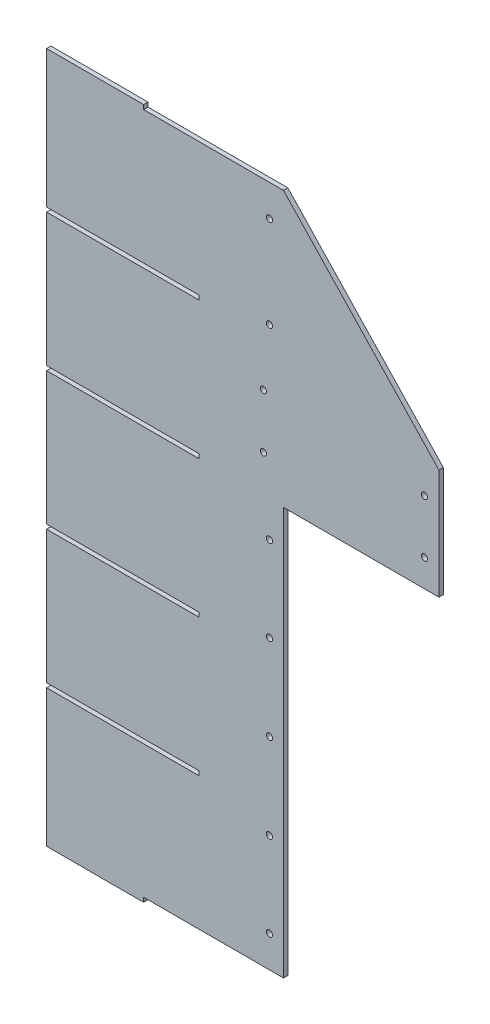
SolidWorks part; units mm, degrees
material "6061-T6 (SS)"
ref_plane "X-Y Datum" through (0, 0, 0) normal (0, 0, 1) x (1, 0, 0)
ref_plane "X-Z Datum" through (0, 0, 0) normal (0, 1, 0) x (1, 0, 0)
ref_plane "Y-Z Datum" through (0, 0, 0) normal (1, 0, 0) x (0, 0, -1)
sketch "Sketch1" plane through (0, 0, 0) normal (0, 0, 1) x (1, 0, 0)
  line L1 (129.0131, 254.2454) -> (-18.6854, 254.2454)
  line L3 (129.0131, -241.3467) -> (-18.6854, -241.3467)
  line L4 (-18.6854, 254.2454) -> (-18.6854, 157.667)
  line L24 (129.0131, 254.2454) -> (129.0131, -241.3467)
  line L25 (92.0885, 157.667) -> (-18.6854, 157.667)
  line L27 (92.0885, 154.492) -> (-18.6854, 154.492)
  line L29 (92.0885, 57.9136) -> (-18.6854, 57.9136)
  line L31 (92.0885, 54.7386) -> (-18.6854, 54.7386)
  line L33 (92.0885, -41.8399) -> (-18.6854, -41.8399)
  line L35 (92.0885, -45.0149) -> (-18.6854, -45.0149)
  line L37 (92.0885, -141.5933) -> (-18.6854, -141.5933)
  line L39 (92.0885, -144.7683) -> (-18.6854, -144.7683)
  line L41 (92.0885, -141.5933) -> (92.0885, -144.7683)
  line L42 (92.0885, -41.8399) -> (92.0885, -45.0149)
  line L43 (92.0885, 57.9136) -> (92.0885, 54.7386)
  line L44 (-18.6854, -144.7683) -> (-18.6854, -241.3467)
  line L45 (-18.6854, -45.0149) -> (-18.6854, -141.5933)
  line L46 (-18.6854, 54.7386) -> (-18.6854, -41.8399)
  line L47 (-18.6854, 154.492) -> (-18.6854, 57.9136)
  line L48 (92.0885, 157.667) -> (92.0885, 154.492)
extrude "Boss-Extrude2" add sketch "Sketch1" along normal blind 3.175
sketch "Sketch4" plane through (0, 0, 3.175) normal (0, 0, 1) x (1, 0, 0)
  line L0 (129.0131, 254.2454) -> (153.4072, 240.1614) construction
  line L2 (129.0131, 254.2454) -> (129.0131, -241.3467)
  line L4 (153.4072, 240.1614) -> (153.4072, -227.2627)
  line L6 (153.4072, -227.2627) -> (153.4072, -241.3467)
  line L7 (153.4072, -241.3467) -> (129.0131, -241.3467)
  line L8 (129.0131, 254.2454) -> (153.4072, 254.2454)
  line L9 (153.4072, 254.2454) -> (153.4072, 240.1614)
extrude "Boss-Extrude3" add sketch "Sketch4" against normal through all
sketch "Sketch7" plane through (0, 0, 3.175) normal (0, 0, 1) x (1, 0, 0)
  line L0 (51.8072, -241.3467) -> (-18.6854, -241.3467)
  line L1 (51.8072, -244.5217) -> (51.8072, -241.3467)
  line L2 (153.4072, -244.5217) -> (51.8072, -244.5217)
  line L3 (153.4072, -244.5217) -> (153.4072, -257.2217)
  line L4 (153.4072, -257.2217) -> (30.4963, -257.2217)
  line L5 (30.4963, -257.2217) -> (6.7146, -273.4777)
  line L6 (-18.6854, -273.4777) -> (6.7146, -273.4777)
  line L7 (-18.6854, -241.3467) -> (-18.6854, -273.4777)
  point P0 (-51.634, -260.9767)
  point P9 (-18.6854, -241.3467)
extrude "Boss-Extrude6" [suppressed] add sketch "Sketch7" against normal through all
sketch "Sketch8" [suppressed] plane through (0, 0, 3.175) normal (0, 0, 1) x (1, 0, 0)
  line L1 (153.4072, -257.2217) -> (221.7231, -257.2217)
  line L2 (153.4072, -257.2217) -> (153.4072, -244.5217)
  line L3 (153.4072, -244.5217) -> (221.7231, -244.5217)
  line L4 (221.7231, -257.2217) -> (221.7231, -244.5217)
  line L5 (153.4072, -241.3467) -> (221.7231, -241.3467)
  line L6 (153.4072, -241.3467) -> (153.4072, -144.7683)
  line L7 (153.4072, -144.7683) -> (221.7231, -144.7683)
  line L8 (221.7231, -241.3467) -> (221.7231, -144.7683)
  dimension "D1" = 68.3158
extrude "Boss-Extrude7" [suppressed] add sketch "Sketch8" against normal through all
sketch "Sketch11" plane through (0, 0, 3.175) normal (0, 0, 1) x (1, 0, 0)
  line L0 (92.0885, 54.7386) -> (153.4072, 54.7386) construction
  line L2 (153.4072, -241.3467) -> (153.4072, 254.2454) construction
  line L3 (266.4372, 134.68) -> (266.4372, 54.7386)
  line L4 (266.4372, 54.7386) -> (153.4072, 54.7386)
  line L5 (153.4072, 54.7386) -> (153.4072, 134.68)
  line L6 (153.4072, -241.3467) -> (153.4072, 254.2454) construction
  line L7 (153.4072, 254.2454) -> (266.4372, 134.68)
  line L8 (153.4072, 254.2454) -> (153.4072, 134.68)
extrude "Boss-Extrude8" add sketch "Sketch11" against normal through all
sketch "Sketch12" plane through (0, 0, 0) normal (0, 0, -1) x (-1, 0, 0)
  line L1 (18.6854, 254.2454) -> (-51.8072, 254.2454)
  line L2 (18.6854, 254.2454) -> (18.6854, 257.4204)
  line L3 (18.6854, 257.4204) -> (-51.8072, 257.4204)
  line L4 (-51.8072, 254.2454) -> (-51.8072, 257.4204)
  line L5 (18.6854, -241.3467) -> (-51.8072, -241.3467)
  line L6 (18.6854, -241.3467) -> (18.6854, -244.5217)
  line L7 (18.6854, -244.5217) -> (-51.8072, -244.5217)
  line L8 (-51.8072, -241.3467) -> (-51.8072, -244.5217)
extrude "Boss-Extrude9" add sketch "Sketch12" against normal through all
sketch "Sketch14" plane through (0, 0, 3.175) normal (0, 0, 1) x (1, 0, 0)
  line L0 (-18.6854, -244.5217) -> (269.694, -244.5217)
  line L1 (-18.6854, -244.5217) -> (-18.6854, 277.9004)
  line L2 (-18.6854, 277.9004) -> (269.694, 277.9004)
  line L3 (269.694, -244.5217) -> (269.694, 277.9004)
  point P0 (143.2472, -231.1146)
  point P1 (143.2472, -158.2226)
  point P2 (143.2472, -85.3305)
  point P3 (143.2472, -12.4385)
  point P4 (143.2472, 60.4536)
  point P5 (170.6792, 87.8856)
  point P6 (210.7117, 87.8856)
  point P7 (250.7441, 87.8856)
  point P8 (256.2772, 93.4187)
  point P9 (256.2772, 119.6462)
  point P10 (256.2772, 145.8738)
  point P11 (143.2472, 173.5725)
  point P12 (143.2472, 208.7929)
  point P13 (143.2472, 244.0133)
sketch "Sketch15" plane through (0, 0, 3.175) normal (0, 0, 1) x (1, 0, 0)
  line L0 (-18.6854, 257.4204) -> (23.3644, 257.4204) construction
  line L1 (-18.6854, 257.4204) -> (-18.6854, 239.7041) construction
  line L2 (-18.6854, 239.7041) -> (23.3644, 239.7041) construction
  line L3 (23.3644, 257.4204) -> (23.3644, 239.7041) construction
  line L4 (258.5632, 130.1671) -> (255.7997, 130.1671) construction
  line L5 (255.7997, 130.1671) -> (255.7997, 113.344) construction
  circle A0 centre (143.2472, 231.3133) radius 2.25
  circle A1 centre (143.2472, 164.652) radius 2.25
  circle A2 centre (255.7997, 113.344) radius 2.25
  circle A3 centre (255.7997, 74.4957) radius 2.25
  circle A4 centre (143.2472, 29.3386) radius 2.25
  circle A5 centre (143.2472, -32.3342) radius 2.25
  circle A6 centre (143.2472, -94.538) radius 2.25
  circle A7 centre (143.2472, -156.7418) radius 2.25
  circle A8 centre (143.2472, -218.4146) radius 2.25
  point P0 (143.2472, 231.3133)
  point P1 (143.2472, 164.652)
  point P2 (255.7997, 113.344)
  point P3 (255.7997, 74.4957)
  point P4 (143.2472, 29.3386)
  point P5 (143.2472, -32.3342)
  point P6 (143.2472, -94.538)
  point P7 (143.2472, -156.7418)
  point P8 (143.2472, -218.4146)
  point P13 (-18.6854, 257.4204)
  point P35 (255.7997, 74.4957)
extrude "Cut-Extrude1" cut sketch "Sketch15" against normal through all
sketch "Sketch16" plane through (0, 0, 3.175) normal (0, 0, 1) x (1, 0, 0)
  line L0 (141.8421, 121.4512) -> (135.7421, 121.4512) construction
  line L1 (141.8421, 82.1409) -> (135.7421, 82.1409) construction
  line L4 (266.4372, 101.236) -> (206.1233, 101.236) construction
  line L5 (206.1233, 134.68) -> (206.1233, 101.236) construction
  circle A0 centre (138.7921, 121.4512) radius 2.25
  circle A1 centre (138.7921, 82.1409) radius 2.25
  point P13 (0, 0)
  point P15 (0, 0)
  point P16 (0, 0)
extrude "Cut-Extrude2" cut sketch "Sketch16" against normal through all
